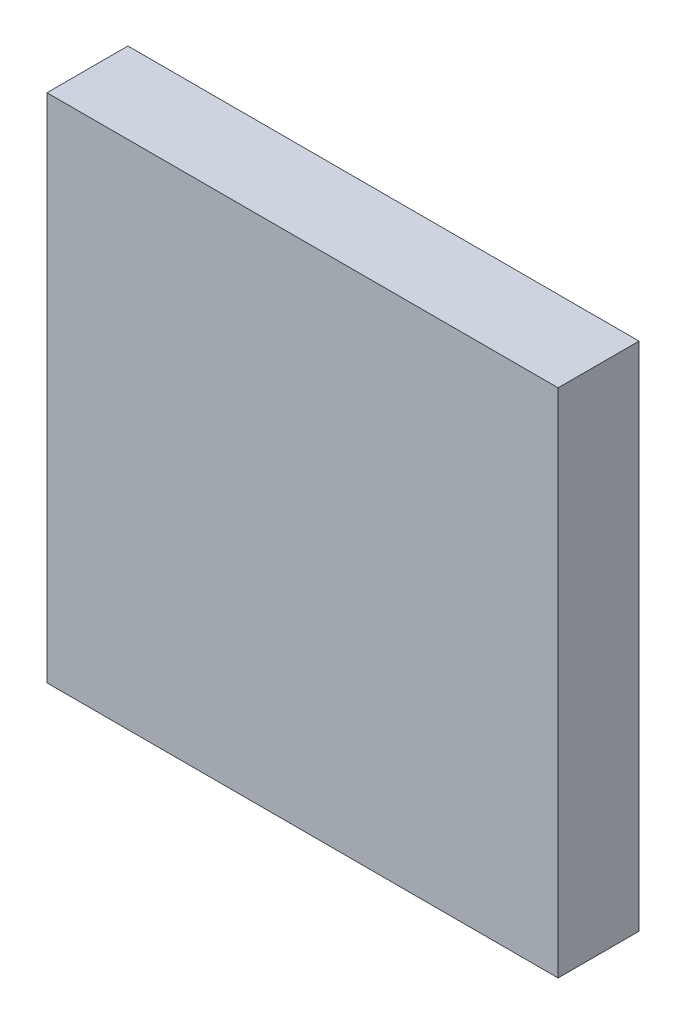
SolidWorks part; units mm, degrees
ref_plane "Front Plane" through (0, 0, 0) normal (0, 0, 1) x (1, 0, 0)
ref_plane "Top Plane" through (0, 0, 0) normal (0, 1, 0) x (1, 0, 0)
ref_plane "Right Plane" through (0, 0, 0) normal (1, 0, 0) x (0, 0, -1)
sketch "Sketch1" plane through (0, 0, 0) normal (0, 0, 1) x (1, 0, 0)
  line L1 (-113.0127, 96.9114) -> (126.9873, 96.9114)
  line L2 (-113.0127, 96.9114) -> (-113.0127, -143.0886)
  line L3 (-113.0127, -143.0886) -> (126.9873, -143.0886)
  line L4 (126.9873, 96.9114) -> (126.9873, -143.0886)
  dimension "D1" = 240
  dimension "D2" = 240
extrude "Boss-Extrude1" add sketch "Sketch1" along normal blind 38
